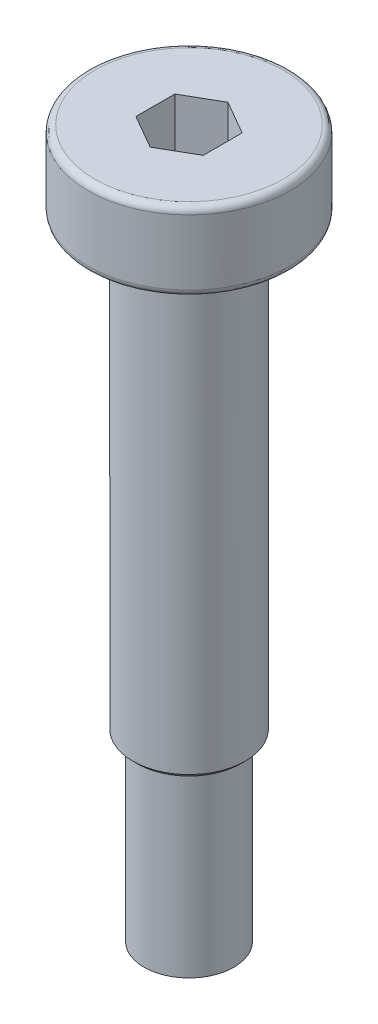
SolidWorks part; units mm, degrees
ref_plane "前视基准面" through (0, 0, 0) normal (0, 0, 1) x (1, 0, 0)
ref_plane "上视基准面" through (0, 0, 0) normal (0, 1, 0) x (1, 0, 0)
ref_plane "右视基准面" through (0, 0, 0) normal (1, 0, 0) x (0, 0, -1)
sketch "草图1" plane through (0, 0, 0) normal (0, 0, 1) x (1, 0, 0)
  line L0 (0, 13.2929) -> (0, -24.3848) construction
  line L1 (0, 9.6164) -> (-4.5, 9.6164)
  line L2 (-4.5, 9.6164) -> (-4.5, 6.1164)
  line L3 (-4.5, 6.1164) -> (-2.5, 6.1164)
  line L4 (-2.5, 6.1164) -> (-2.5, -13.8836)
  line L5 (-2.5, -13.8836) -> (-2, -13.8836)
  line L6 (-2, -13.8836) -> (-2, -21.8836)
  line L7 (-2, -21.8836) -> (0, -21.8836)
  line L8 (0, 9.6164) -> (0, -21.8836)
  point P6 (0, 13.2929)
  point P13 (0, -24.3848)
  dimension "D1" = 4
  dimension "D2" = 8
  dimension "D3" = 5
  dimension "D4" = 9
  dimension "D5" = 3.5
  dimension "D6" = 20
revolve "旋转1" add sketch "草图1" angle 360 about L0
cosmetic thread "装饰螺纹线1" parameters "D2"=3.242
fillet "圆角1" radius 0.3 2 edges at (0, 6.1164, 4.5) (0, 9.6164, 4.5)
sketch "草图2" plane through (0, 9.6164, 0) normal (0, 1, 0) x (1, 0, 0)
  line L1 (1.5, 0.866) -> (0, 1.7321)
  line L2 (0, 1.7321) -> (-1.5, 0.866)
  line L3 (-1.5, 0.866) -> (-1.5, -0.866)
  line L4 (-1.5, -0.866) -> (0, -1.7321)
  line L5 (0, -1.7321) -> (1.5, -0.866)
  line L6 (1.5, -0.866) -> (1.5, 0.866)
  circle A0 centre (0, 0) radius 1.5 construction
  dimension "D1" = 3
extrude "切除-拉伸1" cut sketch "草图2" against normal blind 2.4
chamfer "倒角1" distance 0.2 angle 45 1 edges at (0, -13.8836, 2.5)
